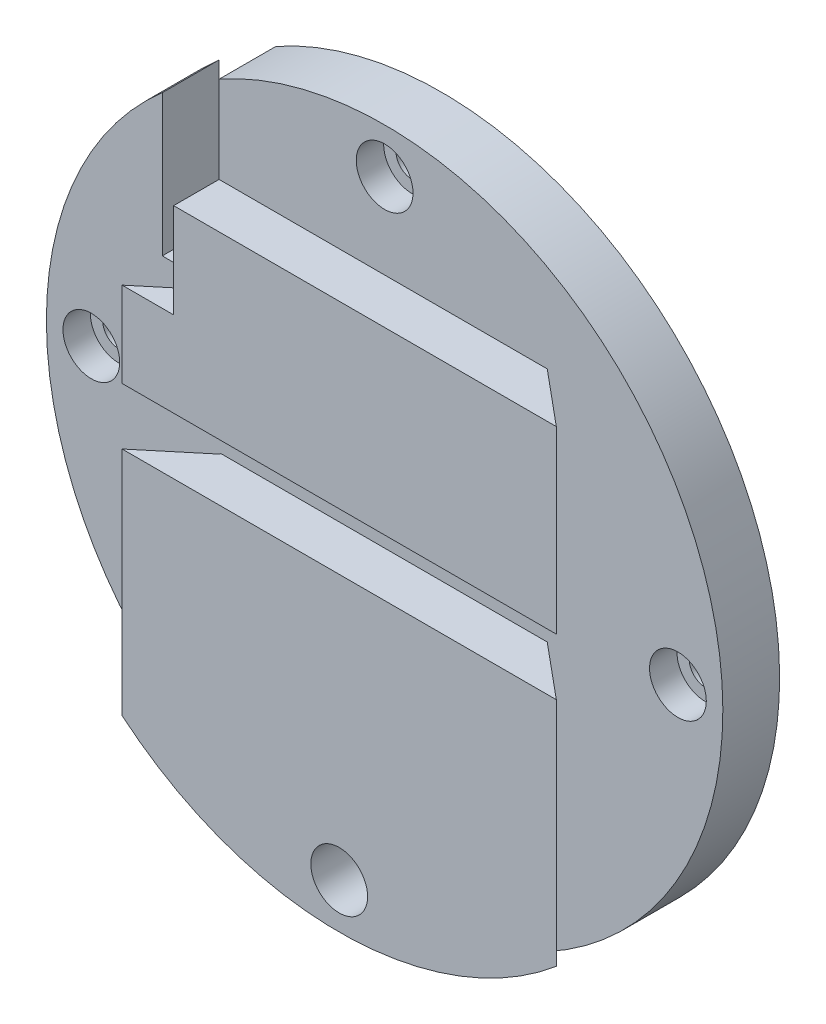
SolidWorks part; units mm, degrees
ref_plane "前视基准面" through (0, 0, 0) normal (0, 0, 1) x (1, 0, 0)
ref_plane "上视基准面" through (0, 0, 0) normal (0, 1, 0) x (1, 0, 0)
ref_plane "右视基准面" through (0, 0, 0) normal (1, 0, 0) x (0, 0, -1)
other "Configuration Table"
sketch "Sketch1" plane through (0, 0, 0) normal (0, 0, 1) x (1, 0, 0)
  line L0 (0, 0) -> (0, 31)
  line L1 (0, 0) -> (31, 0)
  circle A0 centre (0, 0) radius 35.75
  circle A1 centre (0, 31) radius 1.7
  circle A2 centre (31, 0) radius 1.7
  circle A3 centre (0, -31) radius 1.7
  circle A4 centre (-31, 0) radius 1.7
  dimension "D1" = 71.5
  dimension "D3" = 3.4
  dimension "D4" = 3.4
  dimension "D2" = 31
  dimension "D5" = 31
extrude "Boss-Extrude1" add sketch "Sketch1" along normal blind 10.8
sketch "Sketch2" plane through (0, 0, 10.8) normal (0, 0, 1) x (1, 0, 0)
  line L0 (0, 0) -> (-6.1305, 0)
  line L1 (0, 0) -> (0, 9.7918)
  circle A0 centre (0, 31) radius 3
  circle A1 centre (-31, 0) radius 3
  circle A2 centre (31, 0) radius 3
  circle A3 centre (0, -31) radius 3
  circle M4 centre (31, 0) radius 1.7
  circle M6 centre (0, -31) radius 1.7
  circle M8 centre (-31, 0) radius 1.7
  dimension "D1" = 6
  dimension "D2" = 6
extrude "Cut-Extrude1" cut sketch "Sketch2" against normal blind 7.7 contours A1 M8 | A2 M4 | A3 M6 | A0
sketch "Sketch3" plane through (0, 0, 10.8) normal (0, 0, 1) x (1, 0, 0)
  line L0 (0, 0) -> (-17.5, 0)
  line L1 (-17.5, 0) -> (-17.5, 12)
  line L2 (-17.5, 12) -> (-17.5, 22)
  line L3 (-17.5, 22) -> (-23.5, 22)
  line L4 (-23.5, 22) -> (-23.5, 12)
  line L5 (-23.5, 12) -> (-17.5, 12)
  dimension "D1" = 17.5
  dimension "D2" = 12
  dimension "D3" = 10
  dimension "D4" = 6
extrude "Cut-Extrude2" cut sketch "Sketch3" against normal through all contours L4 L5 L2 L3
sketch "Sketch4" plane through (0, 0, 0) normal (0, 1, 0) x (1, 0, 0)
  line L0 (0, 0) -> (0, -6)
  line L1 (0, -6) -> (-17.3, -6)
  line L5 (-17.3, -6) -> (-23.06, -10.8)
  line L6 (-23.06, -10.8) -> (-17.3, -10.8)
  line L7 (-17.3, -10.8) -> (-17.3, -6)
  line L8 (-23.06, -10.8) -> (-35.75, -10.8)
  line L9 (-35.75, -10.8) -> (-35.75, -6)
  line L10 (23.06, -10.8) -> (35.75, -10.8)
  line L11 (-35.75, 0) -> (-35.75, -10.8) construction
  line L12 (-35.75, -6) -> (-17.3, -6)
  line L13 (35.75, -10.8) -> (35.75, -6)
  line L14 (35.75, -6) -> (17.3, -6)
  line L15 (17.3, -6) -> (23.06, -10.8)
  line L16 (0, -6) -> (-17.5, -6)
  line L17 (-17.5, -6) -> (-23.26, -10.8)
  line L18 (-17.1876, -6) -> (-22.9476, -10.8)
  line L19 (17.1876, -6) -> (22.9476, -10.8)
  line L20 (17.3, -6) -> (17.1876, -6)
  line L21 (23.06, -10.8) -> (22.9476, -10.8)
  dimension "D1" = 17.3
  dimension "D2" = 4.8
  dimension "D3" = 5.76
  dimension "D4" = 6
  dimension "D5" = 4.8
  dimension "D6" = 0.2
  dimension "D7" = 0.2
extrude "Cut-Extrude3" cut sketch "Sketch4" against normal through all and the other way up to surface contours L14 L15 L10 L13 | L21 L15 L20 L19 | L17 L12 L9 L8 | L12 L17 L8 L5 | L18 L7 L5 L6 other way up to face at (-20.5, 22, 5.4)
sketch "Sketch5" plane through (-17.5, 0, 0) normal (-1, 0, 0) x (0, 0, 1)
  line L0 (6.1667, 22) -> (4.6144, 22)
  line L1 (4.6144, 22) -> (4.6144, 12)
  line L2 (4.6144, 12) -> (8.5919, 12)
  line L3 (8.5919, 12) -> (8.5919, 22)
  line L4 (6.2603, 22) -> (10.8, 22) construction
  line L5 (8.5919, 22) -> (6, 22)
  line L6 (6.2603, 12) -> (10.8, 12) construction
extrude "Boss-Extrude2" add sketch "Sketch5" against normal blind 7.7
sketch "Sketch6" plane through (-17.5, 0, 0) normal (-1, 0, 0) x (0, 0, 1)
  line L0 (10.8, 22) -> (6, 22)
  line L1 (6, 22) -> (6, 39.275)
  line L2 (6, 39.275) -> (10.8, 39.275)
  line L3 (10.8, 39.275) -> (10.8, 22)
extrude "Cut-Extrude4" cut sketch "Sketch6" against normal through all and the other way through all
sketch "Sketch7" plane through (-17.5, 0, 0) normal (-1, 0, 0) x (0, 0, 1)
  line L0 (0, 0) -> (6, 0)
  line L1 (0, 35.75) -> (0, -35.75) construction
  line L2 (6, 0) -> (6, 3)
  line L3 (6, 3) -> (10.8, 3)
  line L5 (10.8, 3) -> (10.8, -3)
  line L6 (10.8, -3) -> (6, -3)
  line L7 (6, -3) -> (6, 0)
  line L9 (10.8, -27.413) -> (10.8, 12) construction
  dimension "D1" = 3
  dimension "D2" = 3
  dimension "D3" = 6
extrude "Cut-Extrude5" cut sketch "Sketch7" against normal through all and the other way through all contours L7 L6 L5 L3 L2
sketch "Sketch8" plane through (0, 0, 0) normal (0, 0, -1) x (-1, 0, 0)
  line L0 (23.5, 12) -> (17.5, 12) construction
  line L1 (23.5, 22) -> (23.5, 12) construction
  line L2 (17.5, 12) -> (17.5, 22) construction
  line L4 (23.5, 12) -> (17.5, 12)
  line L5 (23.5, 35.0255) -> (23.5, 12)
  line L6 (17.5, 12) -> (17.5, 35.0255)
  line L7 (17.5, 35.0255) -> (23.5, 35.0255)
extrude "Cut-Extrude6" cut sketch "Sketch8" against normal blind 10
